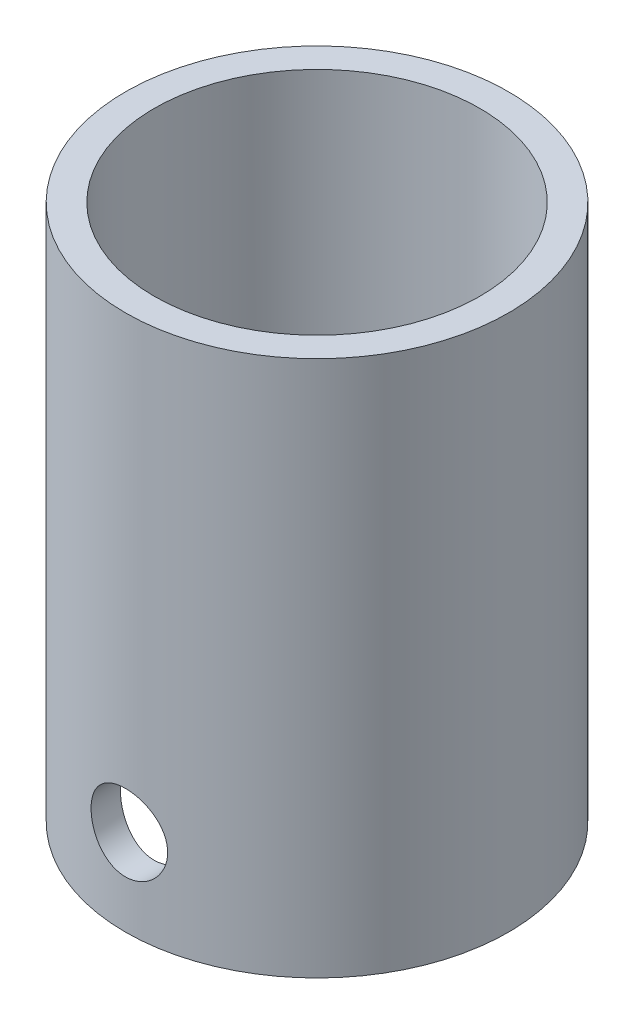
SolidWorks part; units mm, degrees
ref_plane "Спереди" through (0, 0, 0) normal (0, 0, 1) x (1, 0, 0)
ref_plane "Сверху" through (0, 0, 0) normal (0, 1, 0) x (1, 0, 0)
ref_plane "Справа" through (0, 0, 0) normal (1, 0, 0) x (0, 0, -1)
sketch "Эскиз1" plane through (0, 0, 0) normal (0, 1, 0) x (1, 0, 0)
  circle A0 centre (0, 0) radius 8.5
  circle A1 centre (0, 0) radius 10
  dimension "D1" = 20
  dimension "D2" = 17
extrude "тело" add sketch "Эскиз1" along normal blind 28
sketch "Эскиз2" plane through (0, 0, 0) normal (0, 0, 1) x (1, 0, 0)
  line L0 (0, 0) -> (0, 4.5) construction
  circle A0 centre (0, 4.5) radius 2
  dimension "D2" = 4
  dimension "D1" = 4.5
extrude "отверстие чтоб прикрутиться 1" cut sketch "Эскиз2" along normal through all
pattern_circular "Круговой массив1" count 2 every 120 about axis through (0, 28, 0) along (0, -1, 0) of "отверстие чтоб прикрутиться 1"
